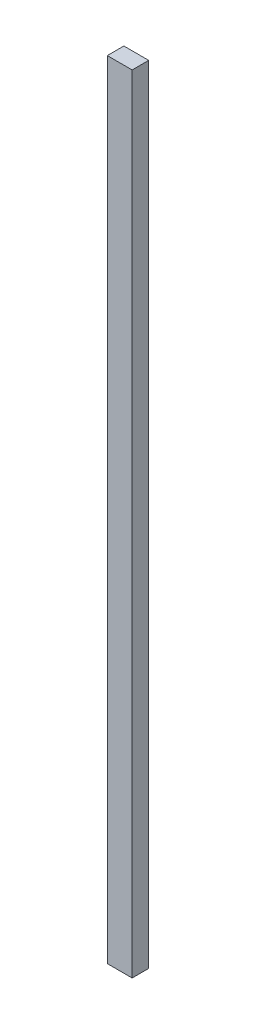
SolidWorks part; units mm, degrees
ref_plane "Front Plane" through (0, 0, 0) normal (0, 0, 1) x (1, 0, 0)
ref_plane "Top Plane" through (0, 0, 0) normal (0, 1, 0) x (1, 0, 0)
ref_plane "Right Plane" through (0, 0, 0) normal (1, 0, 0) x (0, 0, -1)
sketch "Sketch1" plane through (0, 0, -32.8288) normal (0, 0, -1) x (-1, 0, 0)
  line L0 (-29, 201.1294) -> (29, 201.1294) construction
  line L1 (-6, 580.6294) -> (6, 580.6294)
  line L2 (-6, 580.6294) -> (-6, 201.1294)
  line L3 (-6, 201.1294) -> (6, 201.1294)
  line L4 (6, 580.6294) -> (6, 201.1294)
  line L5 (-6, 580.6294) -> (6, 201.1294) construction
  line L6 (-6, 201.1294) -> (6, 580.6294) construction
  line L7 (-29, 201.1294) -> (29, 201.1294) construction
  line L8 (-29, 580.6294) -> (29, 580.6294) construction
  line L9 (-29, 580.6294) -> (29, 580.6294) construction
  line L10 (0, 580.6294) -> (0, 201.1294) construction
  point P0 (0, 390.8794)
  dimension "D1" = 12
extrude "Boss-Extrude1" add sketch "Sketch1" along normal blind 8
